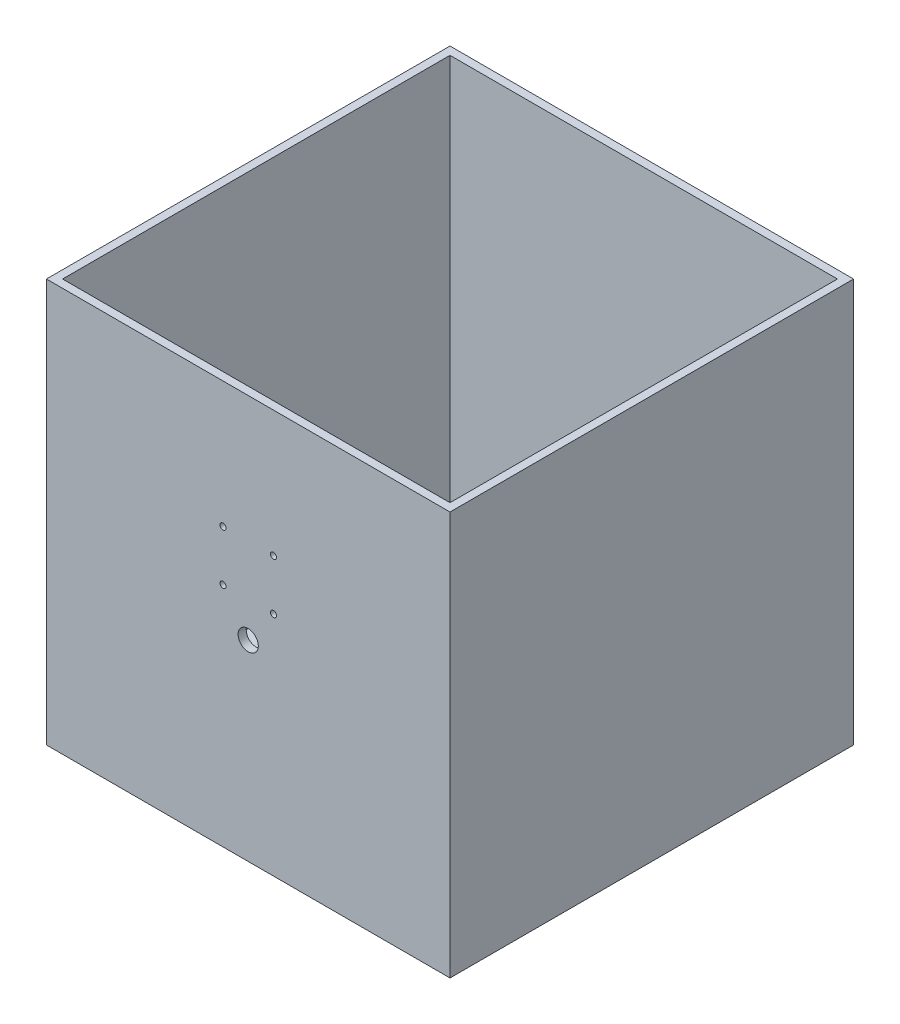
SolidWorks part; units mm, degrees
material "Perspex (TM) GS Acrylic Cast Sheet"
ref_plane "Front Plane" through (0, 0, 0) normal (0, 0, 1) x (1, 0, 0)
ref_plane "Top Plane" through (0, 0, 0) normal (0, 1, 0) x (1, 0, 0)
ref_plane "Right Plane" through (0, 0, 0) normal (1, 0, 0) x (0, 0, -1)
sketch "Sketch1" plane through (0, 0, 0) normal (0, 1, 0) x (1, 0, 0)
  line L1 (-100, -100) -> (100, -100)
  line L2 (-100, -100) -> (-100, 100)
  line L3 (-100, 100) -> (100, 100)
  line L4 (100, -100) -> (100, 100)
  line L5 (-100, -100) -> (100, 100) construction
  line L6 (-100, 100) -> (100, -100) construction
  point P0 (0, 0)
  dimension "D1" = 200
  dimension "D2" = 200
extrude "Boss-Extrude1" add sketch "Sketch1" along normal blind 200
shell "Shell1" thickness 4
sketch "Sketch2" plane through (0, 0, 100) normal (0, 0, 1) x (1, 0, 0)
  line L0 (0, -110) -> (0, 110) construction
  line L1 (-12.5, 112.5) -> (12.5, 112.5) construction
  line L2 (-12.5, 112.5) -> (-12.5, 137.5) construction
  line L3 (-12.5, 137.5) -> (12.5, 137.5) construction
  line L4 (12.5, 112.5) -> (12.5, 137.5) construction
  line L5 (-12.5, 112.5) -> (12.5, 137.5) construction
  line L6 (-12.5, 137.5) -> (12.5, 112.5) construction
  line L7 (-100, 200) -> (100, 200) construction
  circle A0 centre (-12.5, 137.5) radius 1.5
  circle A1 centre (12.5, 137.5) radius 1.5
  circle A2 centre (12.5, 112.5) radius 1.5
  circle A3 centre (-12.5, 112.5) radius 1.5
  circle A4 centre (0, 95) radius 5
  point P0 (0, 125)
  dimension "D4" = 3
  dimension "D5" = 10
  dimension "D1" = 25
  dimension "D2" = 25
  dimension "D3" = 75
  dimension "D6" = 30
extrude "Cut-Extrude1" cut sketch "Sketch2" against normal up to next
sketch "Sketch3" plane through (-100, 0, 0) normal (-1, 0, 0) x (0, 0, 1)
  line L0 (-100, 0) -> (100, 0) construction
  line L1 (-100, 200) -> (-100, 0) construction
  circle A0 centre (-70, 15) radius 3
  dimension "D1" = 6
  dimension "D2" = 15
  dimension "D3" = 30
extrude "Cut-Extrude2" cut sketch "Sketch3" against normal up to next
